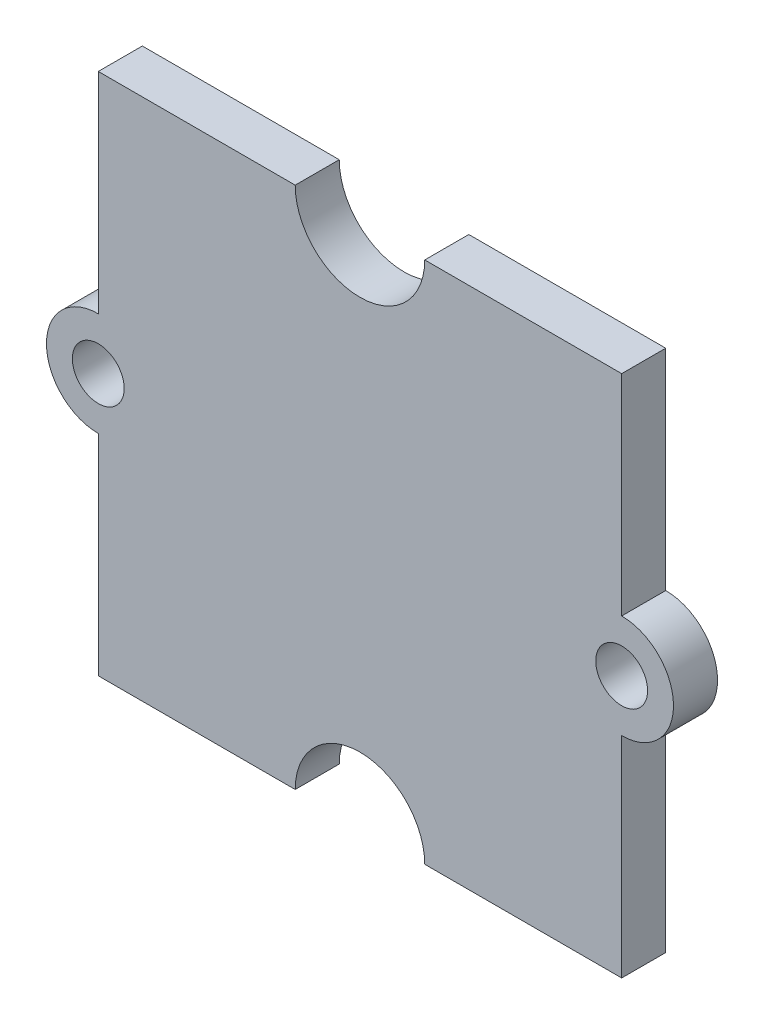
SolidWorks part; units mm, degrees
ref_plane "Alzado" through (0, 0, 0) normal (0, 0, 1) x (1, 0, 0)
ref_plane "Planta" through (0, 0, 0) normal (0, 1, 0) x (1, 0, 0)
ref_plane "Vista lateral" through (0, 0, 0) normal (1, 0, 0) x (0, 0, -1)
sketch "Croquis1" plane through (0, 0, 0) normal (0, 0, 1) x (1, 0, 0)
  line L0 (-2.5, 10.1) -> (-10.1, 10.1)
  line L1 (10.1, -10.1) -> (2.5, -10.1)
  line L2 (10.1, -10.1) -> (10.1, -2)
  line L3 (10.1, 10.1) -> (2.5, 10.1)
  line L4 (-10.1, -10.1) -> (-10.1, -2)
  line L5 (10.1, -10.1) -> (-10.1, 10.1) construction
  line L6 (10.1, 10.1) -> (-10.1, -10.1) construction
  line L7 (-2.5, -10.1) -> (-10.1, -10.1)
  line L8 (-10.1, 2) -> (-10.1, 10.1)
  line L9 (10.1, 2) -> (10.1, 10.1)
  arc A0 (-2.5, 10.1) -> (2.5, 10.1) centre (0, 10.1) ccw
  arc A1 (2.5, -10.1) -> (-2.5, -10.1) centre (0, -10.1) ccw
  arc A2 (-10.1, 2) -> (-10.1, -2) centre (-10.1, 0) ccw
  arc A3 (10.1, -2) -> (10.1, 2) centre (10.1, 0) ccw
  circle A4 centre (-10.1, 0) radius 1
  circle A5 centre (10.1, 0) radius 1
  point P0 (0, 0)
  dimension "D3" = 5
  dimension "D4" = 4
  dimension "D5" = 2
  dimension "D1" = 20.2
  dimension "D2" = 20.2
extrude "Saliente-Extruir1" add sketch "Croquis1" along normal blind 1.7
sketch "Croquis2" plane through (0, 0, 1.7) normal (0, 0, 1) x (1, 0, 0)
  line L0 (0, 7.6) -> (0, -7.6) construction
  line L1 (-2.5, 10.1) -> (-10.1, 10.1) construction
  line L2 (6, 2.9) -> (-6, 2.9)
  line L3 (6, 2.9) -> (6, 8.1)
  line L4 (6, 8.1) -> (-6, 8.1)
  line L5 (-6, 2.9) -> (-6, 8.1)
  line L6 (6, 2.9) -> (-6, 8.1) construction
  line L7 (6, 8.1) -> (-6, 2.9) construction
  line L8 (-5.6, 3.3) -> (-5.6, 7.7)
  line L9 (5.6, 7.7) -> (-5.6, 7.7)
  line L10 (5.6, 3.3) -> (5.6, 7.7)
  line L11 (5.6, 3.3) -> (-5.6, 3.3)
  arc A0 (-2.5, 10.1) -> (2.5, 10.1) centre (0, 10.1) ccw construction
  arc A1 (2.5, -10.1) -> (-2.5, -10.1) centre (0, -10.1) ccw construction
  point P8 (0, 5.5)
  dimension "D1" = 5.2
  dimension "D2" = 12
  dimension "D3" = 2
  dimension "D4" = 0.4
extrude "Saliente-Extruir2" [suppressed] add sketch "Croquis2" along normal blind 9
